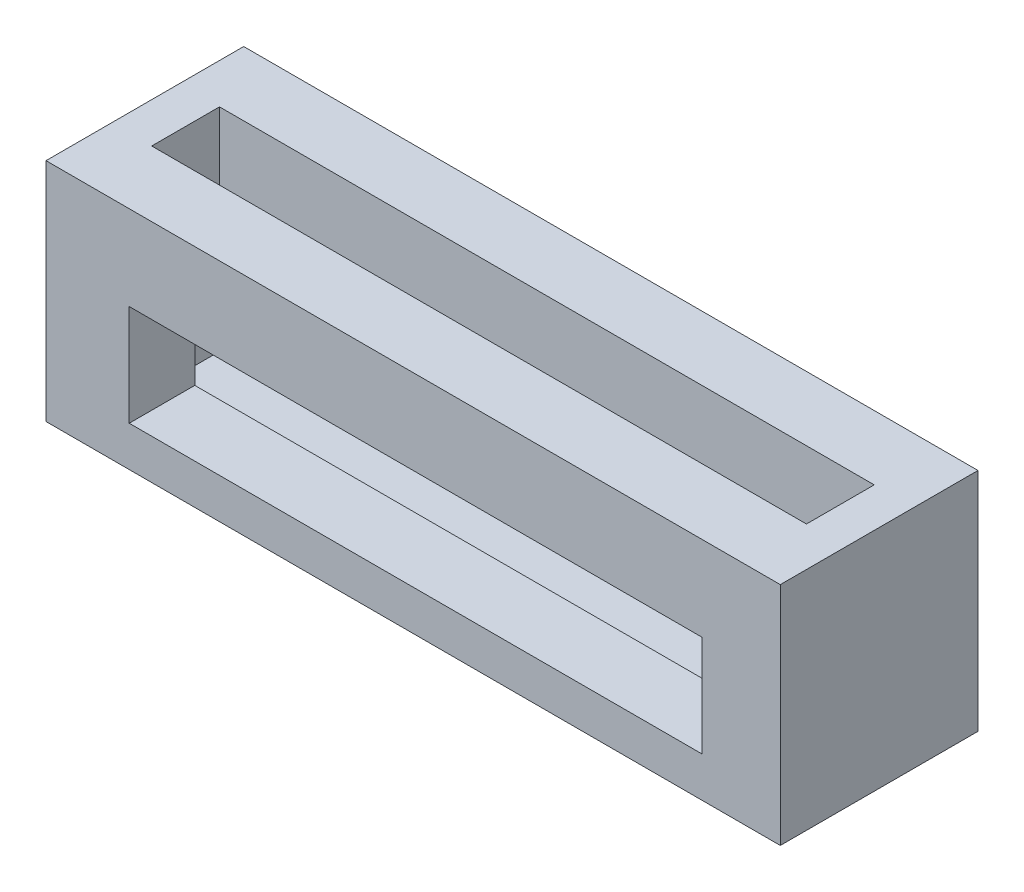
SolidWorks part; units mm, degrees
ref_plane "Plan de face" through (0, 0, 0) normal (0, 0, 1) x (1, 0, 0)
ref_plane "Plan de dessus" through (0, 0, 0) normal (0, 1, 0) x (1, 0, 0)
ref_plane "Plan de droite" through (0, 0, 0) normal (1, 0, 0) x (0, 0, -1)
sketch "Esquisse1" plane through (0, 0, 0) normal (0, 1, 0) x (1, 0, 0)
  line L1 (0, 0) -> (260, 0)
  line L2 (0, 0) -> (0, -70)
  line L3 (0, -70) -> (260, -70)
  line L4 (260, 0) -> (260, -70)
extrude "Boss.-Extru.1" add sketch "Esquisse1" along normal blind 80
ref_plane "Plan3" through (0, 80, 70) normal (1, 0, 0) x (0, 0, -1)
sketch "Esquisse3" plane through (0, 0, 70) normal (0, 0, 1) x (1, 0, 0)
  line L0 (130, 80) -> (130, 50) construction
  line L1 (0, 80) -> (260, 80) construction
  line L3 (29.4672, 50) -> (232.1945, 50)
  line L4 (29.4672, 50) -> (29.4672, 14.2118)
  line L5 (29.4672, 14.2118) -> (232.1945, 14.2118)
  line L6 (232.1945, 50) -> (232.1945, 14.2118)
extrude "Enlèv. mat.-Extru.1" cut sketch "Esquisse3" against normal blind 80 and the other way blind 236 contours L4 L3 L6 L5
sketch "Esquisse4" plane through (0, 80, 0) normal (0, 1, 0) x (1, 0, 0)
  line L0 (0, -32.9802) -> (5, -32.9802) construction
  line L1 (246.0464, -22.7886) -> (14.2191, -22.7886)
  line L2 (246.0464, -22.7886) -> (246.0464, -46.7886)
  line L3 (246.0464, -46.7886) -> (14.2191, -46.7886)
  line L4 (14.2191, -22.7886) -> (14.2191, -46.7886)
  line L5 (0, -141.5) -> (0, 1.5) construction
  line L6 (260, -29.3661) -> (255, -29.3661) construction
  line L7 (260, -70) -> (260, 0) construction
  line L8 (130, 0) -> (130, -70) construction
  line L9 (260, 0) -> (0, 0) construction
  line L10 (0, -70) -> (260, -70) construction
  line L11 (130, -47) -> (130, -23)
  line L12 (61.9445, -12.5107) -> (61.9445, -22.7886) construction
  line L13 (4.6846, -12.5107) -> (255, -12.5107)
  line L14 (4.6846, -12.5107) -> (4.6846, -56.9886)
  line L15 (4.6846, -56.9886) -> (255, -56.9886)
  line L16 (255, -12.5107) -> (255, -56.9886)
  line L17 (67.7827, -46.7886) -> (67.7827, -56.9886) construction
  point P21 (130, -35)
  point P25 (0, 0)
  point P26 (5, -56.0892)
  point P27 (0, 0)
  point P28 (3.9957, -13.631)
  point P29 (4.1256, -57.3876)
  point P30 (0, 0)
  point P35 (0, 0)
  point P36 (3.736, -56.8682)
  point P37 (5, -55.6426)
  point P38 (255, -55.2721)
  point P39 (14.2191, -23.756)
  point P40 (246.0464, -46.5)
  point P41 (0, 0)
  point P42 (255, -56.9886)
  point P43 (255, -12.5107)
extrude "Enlèv. mat.-Extru.2" cut sketch "Esquisse4" against normal blind 75
sketch "Esquisse6" plane through (0, 80, 0) normal (0, 1, 0) x (1, 0, 0)
  line L0 (124.5781, -22.7886) -> (124.5781, -12.7886) construction
  line L1 (6.6511, -12.5774) -> (253.0989, -12.5774)
  line L2 (6.6511, -12.5774) -> (6.6511, -57.8445)
  line L3 (6.6511, -57.8445) -> (253.0989, -57.8445)
  line L4 (253.0989, -12.5774) -> (253.0989, -57.8445)
  line L9 (246.0464, -22.7886) -> (14.2191, -22.7886) construction
  line L10 (124.5781, -12.7886) -> (124.7011, -13.211) construction
  line L12 (124.5781, -46.7886) -> (124.5781, -56.7886) construction
  line L13 (246.0464, -46.7886) -> (14.2191, -46.7886) construction
  line L14 (14.2191, -22.7886) -> (27.2191, -22.7886) construction
  line L15 (246.0464, -22.7886) -> (14.2191, -22.7886) construction
  line L16 (27.2191, -22.7886) -> (40.2191, -22.7886) construction
  line L17 (40.2191, -22.7886) -> (53.2191, -22.7886) construction
  line L18 (53.2191, -22.7886) -> (66.2191, -22.7886) construction
  line L19 (66.2191, -22.7886) -> (79.2191, -22.7886) construction
  line L20 (79.2191, -22.7886) -> (92.2191, -22.7886) construction
  line L21 (92.2191, -22.7886) -> (105.2191, -22.7886) construction
  line L22 (105.2191, -22.7886) -> (118.2191, -22.7886) construction
  line L23 (118.2191, -22.7886) -> (131.2191, -22.7886) construction
  line L24 (131.2191, -22.7886) -> (144.2191, -22.7886) construction
  line L25 (144.2191, -22.7886) -> (157.2191, -22.7886) construction
  line L26 (157.2191, -22.7886) -> (170.2191, -22.7886) construction
  line L27 (170.2191, -22.7886) -> (183.2191, -22.7886) construction
  line L28 (183.2191, -22.7886) -> (196.2191, -22.7886) construction
  line L29 (196.2191, -22.7886) -> (209.2191, -22.7886) construction
  line L30 (209.2191, -22.7886) -> (222.2191, -22.7886) construction
  line L31 (6.6511, -57.8445) -> (105.2191, -183.9713)
  line L32 (253.0989, -57.8445) -> (232.4032, -183.9713)
